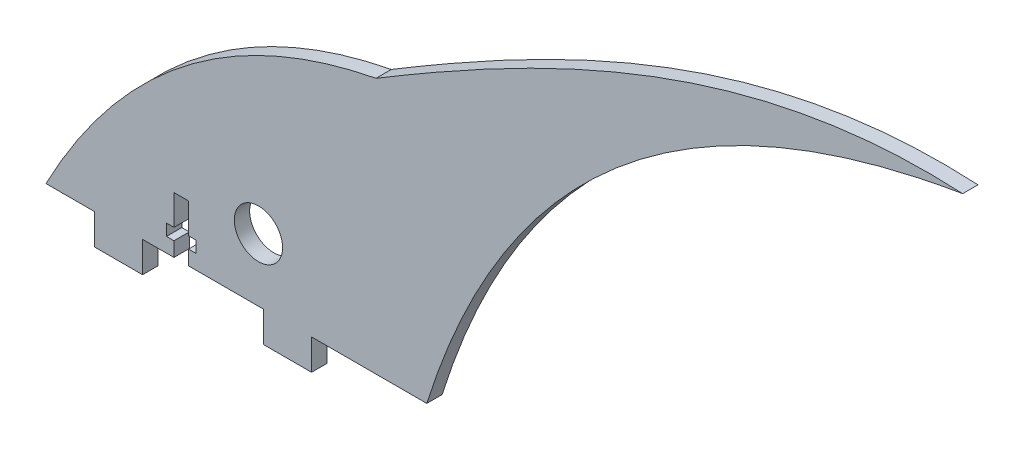
SolidWorks part; units mm, degrees
ref_plane "前视基准面" through (0, 0, 0) normal (0, 0, 1) x (1, 0, 0)
ref_plane "上视基准面" through (0, 0, 0) normal (0, 1, 0) x (1, 0, 0)
ref_plane "右视基准面" through (0, 0, 0) normal (1, 0, 0) x (0, 0, -1)
sketch "Sketch1" plane through (0, 0, 0) normal (0, 0, 1) x (1, 0, 0)
  line L0 (-138.2384, 83.589) -> (435.095, 83.589) construction
sketch "Sketch2" plane through (0, 0, 0) normal (0, 0, 1) x (1, 0, 0)
  line L0 (-100.6099, -40.6042) -> (-21.7448, -40.6042)
  spline S0 degree 3 poles (89.239, 52.5113) (45.2136, 54.9609) (4.5227, 34.5926) (-32.26, 12.4585) knots 0 0 0 0 1 1 1 1
  spline S1 degree 2 poles (-32.26, 12.4585) (-77.3881, 3.7059) (-100.6099, -40.6042) knots 0 0 0 1 1 1
  spline S2 degree 2 poles (89.239, 52.5113) (2.9196, 37.9894) (-21.7448, -40.6042) knots 0 0 0 1 1 1
extrude "Boss-Extrude1" add sketch "Sketch2" along normal blind 3.175
sketch "Sketch3" plane through (0, 0, 3.175) normal (0, 0, 1) x (1, 0, 0)
  line L0 (-90.6099, -40.6042) -> (-90.6099, -46.9542)
  line L1 (-100.6099, -40.6042) -> (-21.7448, -40.6042) construction
  line L2 (-90.6099, -46.9542) -> (-80.6099, -46.9542)
  line L3 (-80.6099, -46.9542) -> (-80.6099, -40.6042)
  line L4 (-80.6099, -40.6042) -> (-90.6099, -40.6042)
  line L5 (-68.1099, -23.5392) -> (-68.1099, -54.0615) construction
  line L6 (-55.6099, -40.6042) -> (-45.6099, -40.6042)
  line L7 (-55.6099, -46.9542) -> (-55.6099, -40.6042)
  line L8 (-45.6099, -46.9542) -> (-55.6099, -46.9542)
  line L9 (-45.6099, -40.6042) -> (-45.6099, -46.9542)
  dimension "D1" = 10
  dimension "D2" = 6.35
  dimension "D3" = 10
  dimension "D4" = 25
extrude "Boss-Extrude2" add sketch "Sketch3" against normal blind 3.175
sketch "Sketch4" plane through (0, 0, 3.175) normal (0, 0, 1) x (1, 0, 0)
  line L0 (-56.6099, -40.6042) -> (-56.6099, -7.4935) construction
  line L1 (-80.6099, -40.6042) -> (-55.6099, -40.6042) construction
  line L2 (-55.6099, -40.6042) -> (-55.6099, -46.9542) construction
  circle A0 centre (-56.6099, -27.6042) radius 5
  dimension "D1" = 10
  dimension "D2" = 1
  dimension "D3" = 13
extrude "Cut-Extrude1" cut sketch "Sketch4" against normal through all
sketch "Sketch5" plane through (0, 0, 3.175) normal (0, 0, 1) x (1, 0, 0)
  line L0 (-72.6099, -22.9295) -> (-72.6099, -73.9872) construction
  line L1 (-74.1099, -37.6042) -> (-74.1099, -40.6042)
  line L2 (-80.6099, -40.6042) -> (-55.6099, -40.6042) construction
  line L3 (-74.1099, -40.6042) -> (-71.1099, -40.6042)
  line L4 (-74.1099, -37.6042) -> (-75.6599, -37.6042)
  line L5 (-75.6599, -37.6042) -> (-75.6599, -35.2042)
  line L6 (-75.6599, -35.2042) -> (-74.1099, -35.2042)
  line L7 (-74.1099, -35.2042) -> (-74.1099, -28.9542)
  line L8 (-74.1099, -28.9542) -> (-71.1099, -28.9542)
  line L9 (-71.1099, -35.2042) -> (-71.1099, -28.9542)
  line L10 (-69.5599, -35.2042) -> (-71.1099, -35.2042)
  line L11 (-69.5599, -37.6042) -> (-69.5599, -35.2042)
  line L12 (-71.1099, -37.6042) -> (-69.5599, -37.6042)
  line L13 (-71.1099, -37.6042) -> (-71.1099, -40.6042)
  line L14 (-90.6099, -46.9542) -> (-80.6099, -46.9542) construction
  line L15 (-80.6099, -46.9542) -> (-80.6099, -40.6042) construction
  point P13 (-72.6099, -28.9542)
  point P18 (-72.6099, -40.6042)
  dimension "D1" = 6.1
  dimension "D2" = 3
  dimension "D3" = 2.4
  dimension "D4" = 18
  dimension "D5" = 3
  dimension "D6" = 8
extrude "Cut-Extrude2" cut sketch "Sketch5" against normal through all
